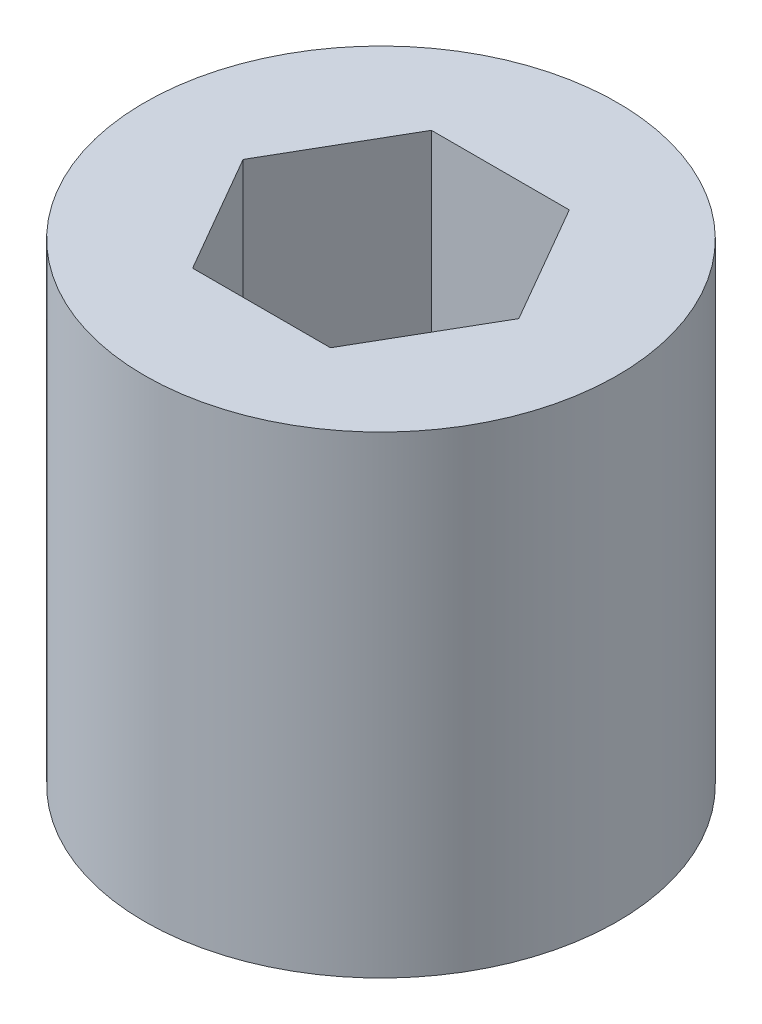
SolidWorks part; units mm, degrees
ref_plane "Front Plane" through (0, 0, 0) normal (0, 0, 1) x (1, 0, 0)
ref_plane "Top Plane" through (0, 0, 0) normal (0, 1, 0) x (1, 0, 0)
ref_plane "Right Plane" through (0, 0, 0) normal (1, 0, 0) x (0, 0, -1)
sketch "Sketch1" plane through (0, 0, 0) normal (0, 1, 0) x (1, 0, 0)
  line L1 (7.4057, 0) -> (3.7028, 6.4135)
  line L2 (3.7028, 6.4135) -> (-3.7028, 6.4135)
  line L3 (-3.7028, 6.4135) -> (-7.4057, 0)
  line L4 (-7.4057, 0) -> (-3.7028, -6.4135)
  line L5 (-3.7028, -6.4135) -> (3.7028, -6.4135)
  line L6 (3.7028, -6.4135) -> (7.4057, 0)
  circle A0 centre (0, 0) radius 12.7
  circle A1 centre (0, 0) radius 6.4135 construction
  dimension "D1" = 12.827
  dimension "D2" = 25.4
extrude "Boss-Extrude1" add sketch "Sketch1" along normal blind 25.4
